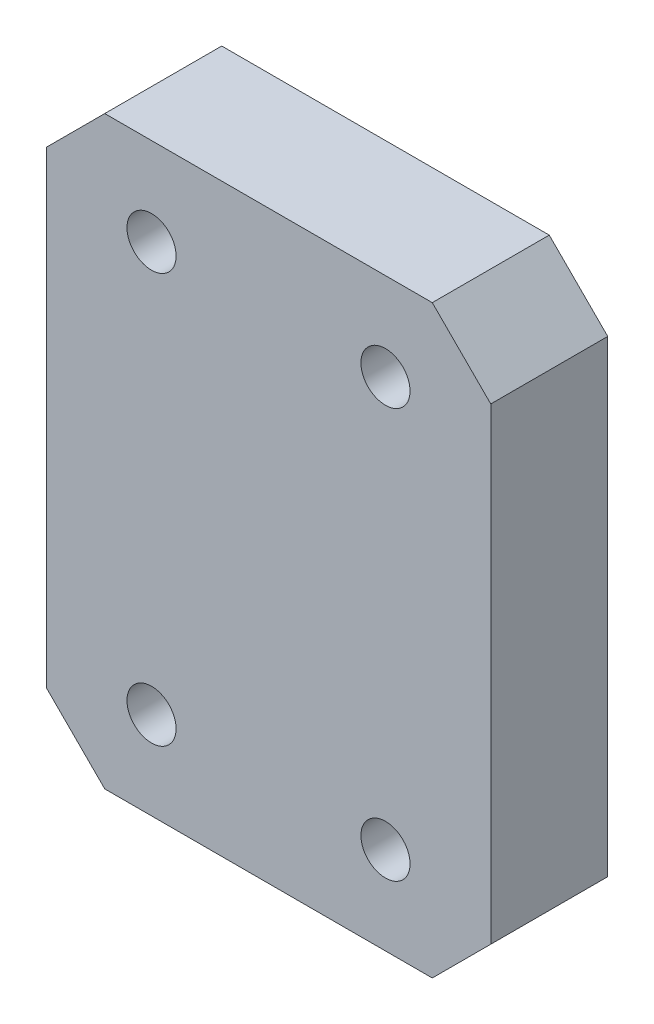
SolidWorks part; units mm, degrees
material "ABS"
ref_plane "前基準面" through (0, 0, 0) normal (0, 0, 1) x (1, 0, 0)
ref_plane "上基準面" through (0, 0, 0) normal (0, 1, 0) x (1, 0, 0)
ref_plane "右基準面" through (0, 0, 0) normal (1, 0, 0) x (0, 0, -1)
sketch "草圖1" plane through (0, 0, 0) normal (0, 0, 1) x (1, 0, 0)
  line L1 (-19, -25) -> (19, -25)
  line L2 (-19, -25) -> (-19, 25)
  line L3 (-19, 25) -> (19, 25)
  line L4 (19, -25) -> (19, 25)
  line L5 (-19, -25) -> (19, 25) construction
  line L6 (-19, 25) -> (19, -25) construction
  point P0 (0, 0)
  dimension "D1" = 38
  dimension "D2" = 50
extrude "填料-伸長1" add sketch "草圖1" along normal blind 10
chamfer "導角1" distance 5 angle 45 4 edges at (-19, -25, 5) (19, -25, 5) (19, 25, 5) (-19, 25, 5)
sketch "草圖2" plane through (0, 0, 0) normal (0, 0, -1) x (-1, 0, 0)
  line L1 (-10, 17.5) -> (10, 17.5) construction
  line L2 (-10, 17.5) -> (-10, -17.5) construction
  line L3 (-10, -17.5) -> (10, -17.5) construction
  line L4 (10, 17.5) -> (10, -17.5) construction
  circle A0 centre (-10, 17.5) radius 2.1
  circle A1 centre (10, 17.5) radius 2.1
  circle A2 centre (-10, -17.5) radius 2.1
  circle A3 centre (10, -17.5) radius 2.1
  point P8 (0, 17.5)
  point P9 (-10, 0)
  dimension "D1" = 4.2
  dimension "D2" = 20
  dimension "D3" = 35
extrude "除料-伸長1" cut sketch "草圖2" against normal up to next
